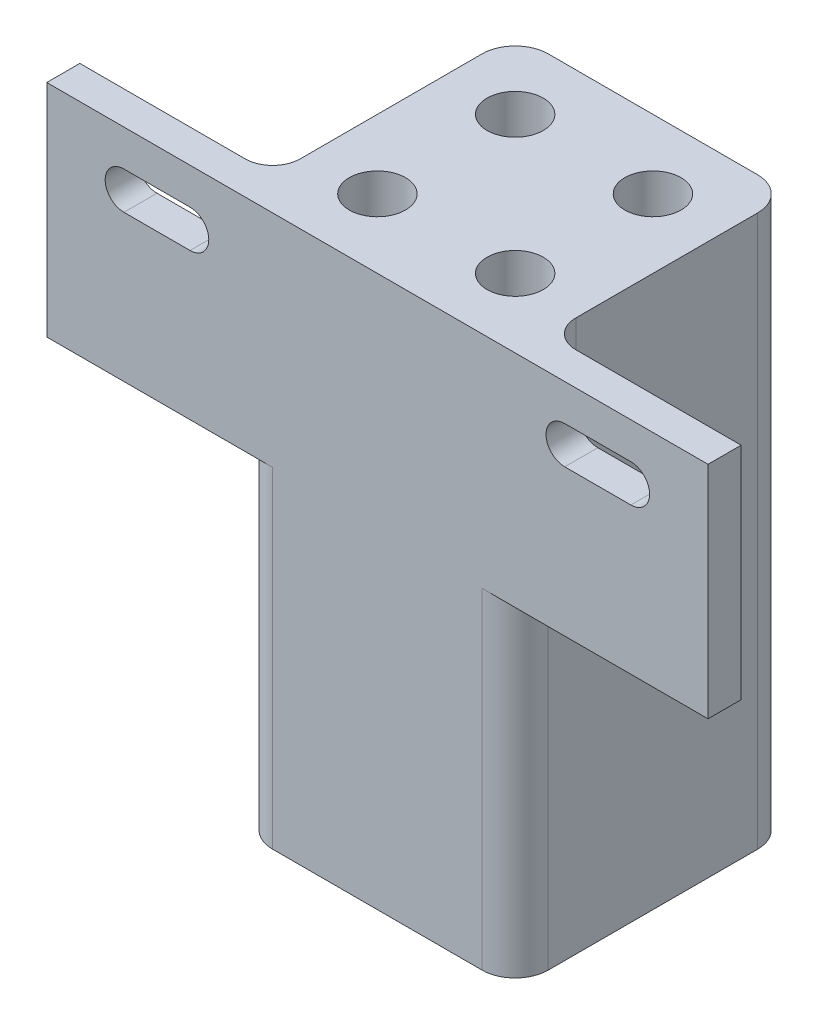
SolidWorks part; units mm, degrees
ref_plane "前视基准面" through (0, 0, 0) normal (0, 0, 1) x (1, 0, 0)
ref_plane "上视基准面" through (0, 0, 0) normal (0, 1, 0) x (1, 0, 0)
ref_plane "右视基准面" through (0, 0, 0) normal (1, 0, 0) x (0, 0, -1)
sketch "草图1" plane through (0, 0, 0) normal (0, 1, 0) x (1, 0, 0)
  line L1 (-9.5, 12.5) -> (9.5, 12.5)
  line L2 (-12.5, 9.5) -> (-12.5, -9.5)
  line L3 (-9.5, -12.5) -> (9.5, -12.5)
  line L4 (12.5, 9.5) -> (12.5, -9.5)
  line L5 (-12.5, 12.5) -> (12.5, -12.5) construction
  line L6 (-12.5, -12.5) -> (12.5, 12.5) construction
  arc A0 (-12.5, -9.5) -> (-9.5, -12.5) centre (-9.5, -9.5) ccw
  arc A1 (9.5, -12.5) -> (12.5, -9.5) centre (9.5, -9.5) ccw
  arc A2 (9.5, 12.5) -> (12.5, 9.5) centre (9.5, 9.5) cw
  arc A3 (-9.5, 12.5) -> (-12.5, 9.5) centre (-9.5, 9.5) ccw
  circle A4 centre (0, 0) radius 8.8388 construction
  circle A5 centre (6.25, 6.25) radius 2.55
  circle A6 centre (-6.25, 6.25) radius 2.55
  circle A7 centre (-6.25, -6.25) radius 2.55
  circle A8 centre (6.25, -6.25) radius 2.55
  point P0 (0, 0)
  dimension "D1" = 3
  dimension "D3" = 5.1
  dimension "D2" = 25
  dimension "D4" = 12.5
extrude "凸台-拉伸1" add sketch "草图1" along normal blind 30
sketch "草图2" plane through (0, 30, 0) normal (0, 1, 0) x (1, 0, 0)
  line L0 (-9.5, -12.5) -> (-30, -12.5)
  line L1 (-30, -12.5) -> (-30, -9.5)
  line L2 (-30, -9.5) -> (-12.5, -9.5)
  line L3 (9.5, -12.5) -> (30, -12.5)
  line L4 (-9.5, -12.5) -> (9.5, -12.5)
  line L5 (12.5, -9.5) -> (12.5, 9.5)
  line L6 (9.5, 12.5) -> (-9.5, 12.5)
  line L7 (-12.5, 9.5) -> (-12.5, -9.5)
  line L8 (-9.5, -12.5) -> (9.5, -12.5)
  line L9 (12.5, -9.5) -> (12.5, 9.5)
  line L10 (9.5, 12.5) -> (-9.5, 12.5)
  line L11 (-12.5, 9.5) -> (-12.5, -9.5)
  line L12 (30, -12.5) -> (30, -9.5)
  line L13 (30, -9.5) -> (12.5, -9.5)
  line L14 (0, 0) -> (0, -6.6545) construction
  circle A0 centre (-6.25, 6.25) radius 2.55 construction
  circle A1 centre (-6.25, 6.25) radius 2.55
  circle A2 centre (6.25, 6.25) radius 2.55 construction
  circle A3 centre (6.25, 6.25) radius 2.55
  arc A4 (-12.5, -9.5) -> (-9.5, -12.5) centre (-9.5, -9.5) ccw
  arc A5 (9.5, -12.5) -> (12.5, -9.5) centre (9.5, -9.5) ccw
  arc A6 (12.5, 9.5) -> (9.5, 12.5) centre (9.5, 9.5) ccw
  arc A7 (-9.5, 12.5) -> (-12.5, 9.5) centre (-9.5, 9.5) ccw
  arc A10 (12.5, 9.5) -> (9.5, 12.5) centre (9.5, 9.5) ccw
  arc A11 (-9.5, 12.5) -> (-12.5, 9.5) centre (-9.5, 9.5) ccw
  circle A12 centre (-6.25, -6.25) radius 2.55 construction
  circle A13 centre (-6.25, -6.25) radius 2.55
  circle A14 centre (6.25, -6.25) radius 2.55 construction
  circle A15 centre (6.25, -6.25) radius 2.55
  dimension "D2" = 3
  dimension "D3" = 60
  dimension "D1" = 0
extrude "凸台-拉伸2" add sketch "草图2" along normal blind 20
sketch "草图3" plane through (0, 0, 9.5) normal (0, 0, -1) x (-1, 0, 0)
  line L0 (-20, 45) -> (20, 45) construction
  line L1 (0, 45) -> (0, 50) construction
  line L2 (-9.5, 50) -> (9.5, 50) construction
  line L3 (-23, 45) -> (-17, 45) construction
  line L4 (-23, 46.7) -> (-17, 46.7)
  line L5 (-23, 43.3) -> (-17, 43.3)
  line L6 (23, 45) -> (17, 45) construction
  line L7 (23, 43.3) -> (17, 43.3)
  line L8 (23, 46.7) -> (17, 46.7)
  arc A0 (-23, 46.7) -> (-23, 43.3) centre (-23, 45) ccw
  arc A1 (-17, 43.3) -> (-17, 46.7) centre (-17, 45) ccw
  arc A2 (23, 43.3) -> (23, 46.7) centre (23, 45) ccw
  arc A3 (17, 46.7) -> (17, 43.3) centre (17, 45) ccw
  point P8 (-20, 45)
  point P14 (20, 45)
  dimension "D1" = 3.4
  dimension "D2" = 6
  dimension "D3" = 40
  dimension "D4" = 5
extrude "切除-拉伸1" cut sketch "草图3" against normal blind 20
fillet "圆角1" radius 2.5 2 edges at (-12.5, 40, 9.5) (12.5, 40, 9.5)
